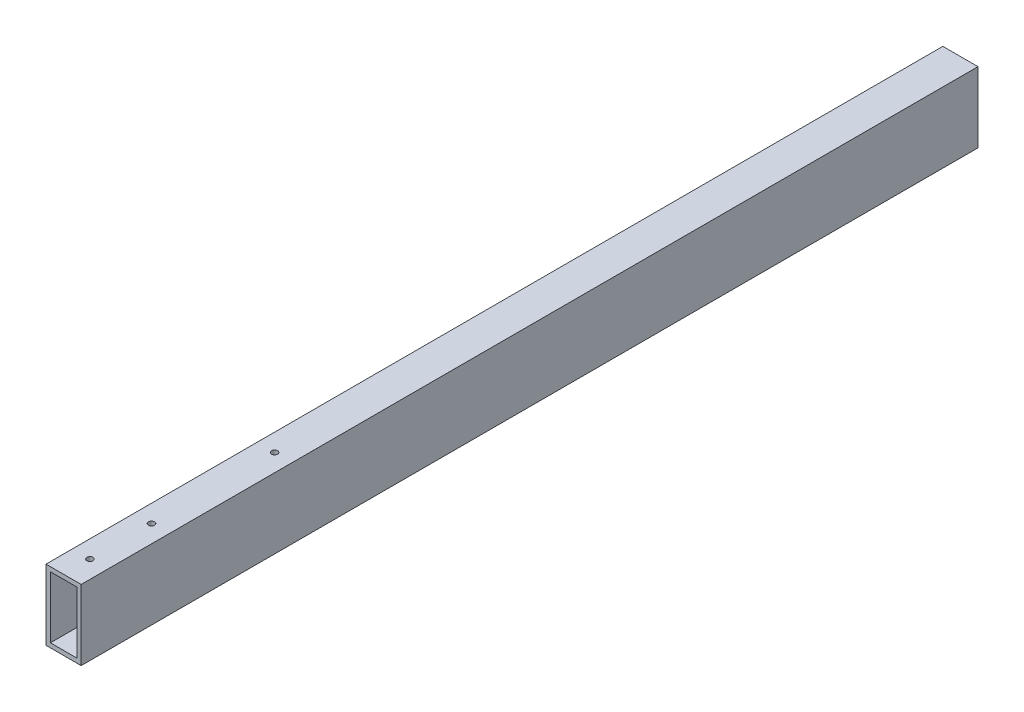
SolidWorks part; units mm, degrees
material "6061-T4 (SS)"
ref_plane "Front Plane" through (0, 0, 0) normal (0, 0, 1) x (1, 0, 0)
ref_plane "Top Plane" through (0, 0, 0) normal (0, 1, 0) x (1, 0, 0)
ref_plane "Right Plane" through (0, 0, 0) normal (1, 0, 0) x (0, 0, -1)
sketch "Sketch1" plane through (0, 0, 0) normal (0, 0, 1) x (1, 0, 0)
  line L0 (-9.525, 22.225) -> (9.525, 22.225)
  line L1 (-12.7, 25.4) -> (12.7, 25.4)
  line L2 (-12.7, 25.4) -> (-12.7, -25.4)
  line L3 (-12.7, -25.4) -> (12.7, -25.4)
  line L4 (12.7, 25.4) -> (12.7, -25.4)
  line L5 (-12.7, 25.4) -> (12.7, -25.4) construction
  line L6 (-12.7, -25.4) -> (12.7, 25.4) construction
  line L7 (9.525, 22.225) -> (9.525, -22.225)
  line L8 (-9.525, -22.225) -> (9.525, -22.225)
  line L9 (-9.525, 22.225) -> (-9.525, -22.225)
  point P0 (0, 0)
  dimension "D1" = 50.8
  dimension "D2" = 25.4
  dimension "D3" = 3.175
extrude "Boss-Extrude1" add sketch "Sketch1" along normal mid plane 647.7
sketch "Sketch2" plane through (0, 25.4, 0) normal (0, 1, 0) x (1, 0, 0)
  circle A0 centre (0.0001, -304.8) radius 2.1971
  circle A1 centre (0.0001, -260.35) radius 2.1971
  circle A2 centre (0.0001, -171.45) radius 2.1971
  point P8 (0, 0)
  point P9 (0, 0)
  point P10 (0.0001, -260.35)
  point P13 (0.2448, -304.6607)
  point P14 (0.0001, -304.8)
  dimension "D1" = 4.3942
extrude "Cut-Extrude1" cut sketch "Sketch2" against normal up to surface (50.8 mm away) up to face at (0, -25.4, 0)
